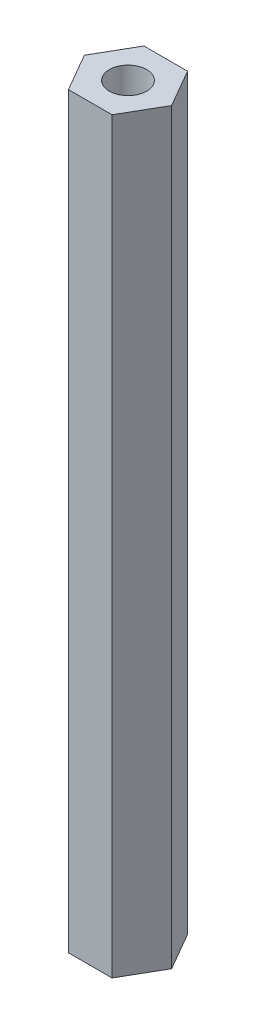
SolidWorks part; units mm, degrees
material "6061-T6 (SS)"
ref_plane "Front Plane" through (0, 0, 0) normal (0, 0, 1) x (1, 0, 0)
ref_plane "Top Plane" through (0, 0, 0) normal (0, 1, 0) x (1, 0, 0)
ref_plane "Right Plane" through (0, 0, 0) normal (1, 0, 0) x (0, 0, -1)
sketch "Sketch1" plane through (0, 0, 0) normal (0, 1, 0) x (1, 0, 0)
  line L1 (-3.4987, 0) -> (-1.7493, -3.0299)
  line L2 (-1.7493, -3.0299) -> (1.7493, -3.0299)
  line L3 (1.7493, -3.0299) -> (3.4987, 0)
  line L4 (3.4987, 0) -> (1.7493, 3.0299)
  line L5 (1.7493, 3.0299) -> (-1.7493, 3.0299)
  line L6 (-1.7493, 3.0299) -> (-3.4987, 0)
  circle A0 centre (0, 0) radius 1.5
  circle A1 centre (0, 0) radius 3.0299 construction
extrude "Boss-Extrude1" add sketch "Sketch1" along normal blind 60
